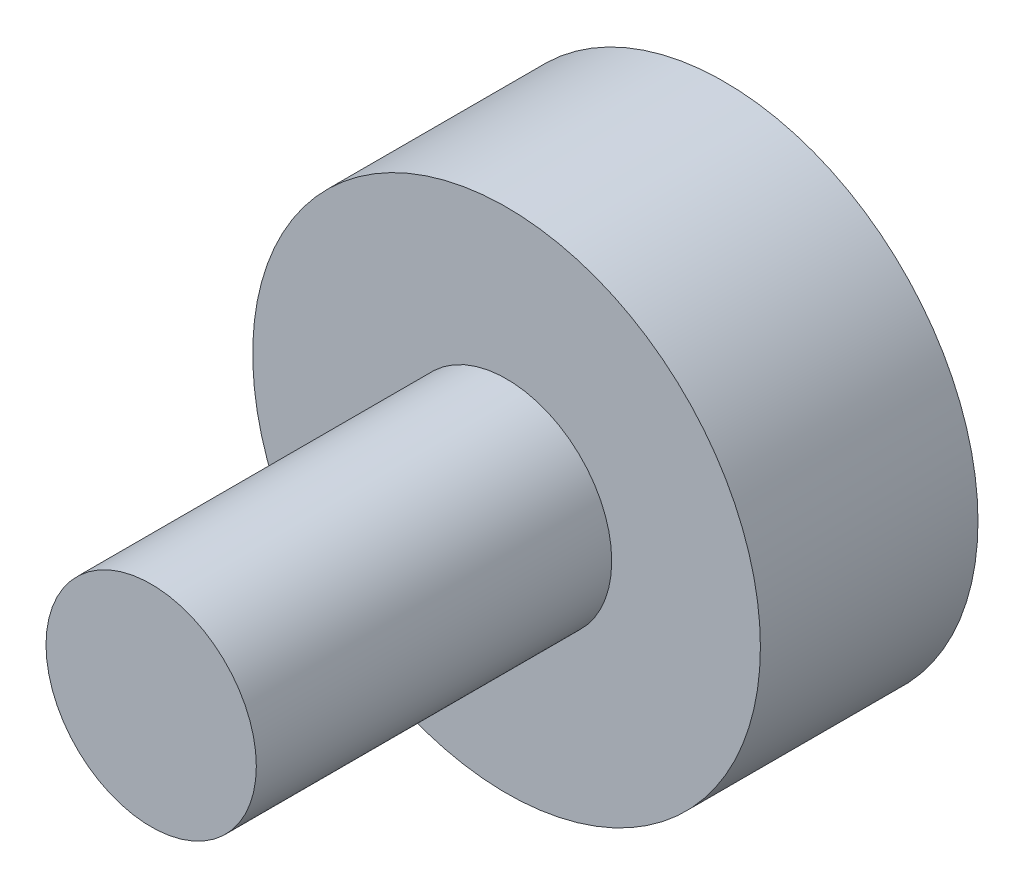
SolidWorks part; units mm, degrees
ref_plane "Front Plane" through (0, 0, 0) normal (0, 0, 1) x (1, 0, 0)
ref_plane "Top Plane" through (0, 0, 0) normal (0, 1, 0) x (1, 0, 0)
ref_plane "Right Plane" through (0, 0, 0) normal (1, 0, 0) x (0, 0, -1)
sketch "Sketch1" plane through (0, 0, 0) normal (0, 0, 1) x (1, 0, 0)
  circle A0 centre (0, 0) radius 3.5
extrude "Boss-Extrude1" add sketch "Sketch1" along normal blind 3
sketch "Sketch2" plane through (0, 0, 3) normal (0, 0, 1) x (1, 0, 0)
  circle A0 centre (0, 0) radius 1.45
  dimension "D1" = 2.9
extrude "Boss-Extrude2" add sketch "Sketch2" along normal blind 4.9
